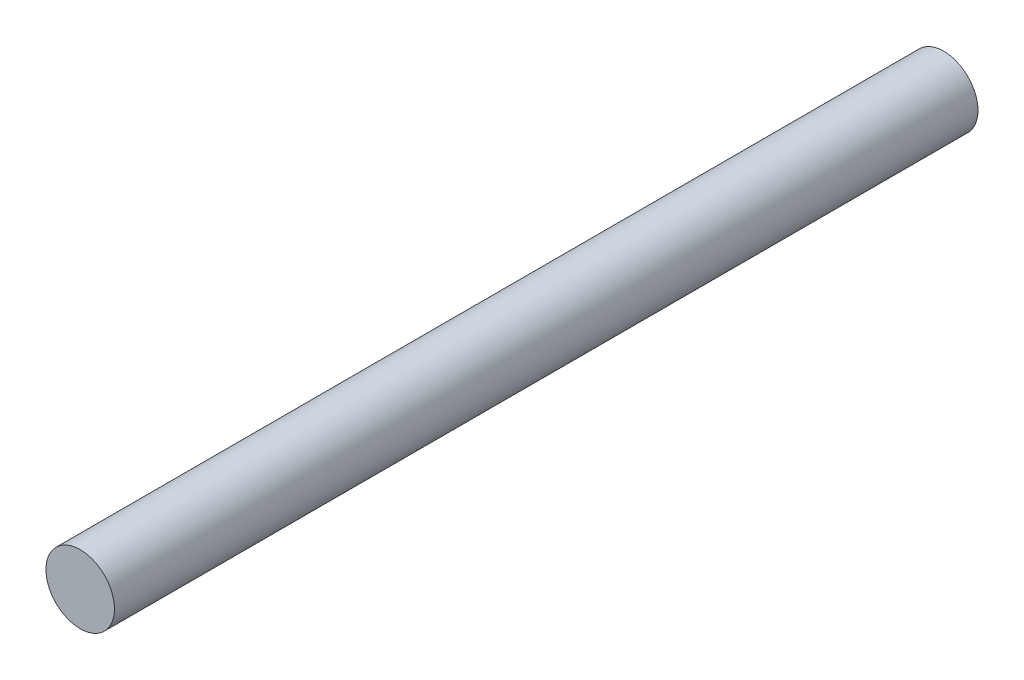
SolidWorks part; units mm, degrees
ref_plane "Front Plane" through (0, 0, 0) normal (0, 0, 1) x (1, 0, 0)
ref_plane "Top Plane" through (0, 0, 0) normal (0, 1, 0) x (1, 0, 0)
ref_plane "Right Plane" through (0, 0, 0) normal (1, 0, 0) x (0, 0, -1)
sketch "Sketch1" plane through (0, 0, 0) normal (0, 0, 1) x (1, 0, 0)
  circle A0 centre (0, 0) radius 6.35
  dimension "D1" = 12.7
extrude "Boss-Extrude1" add sketch "Sketch1" along normal blind 160
